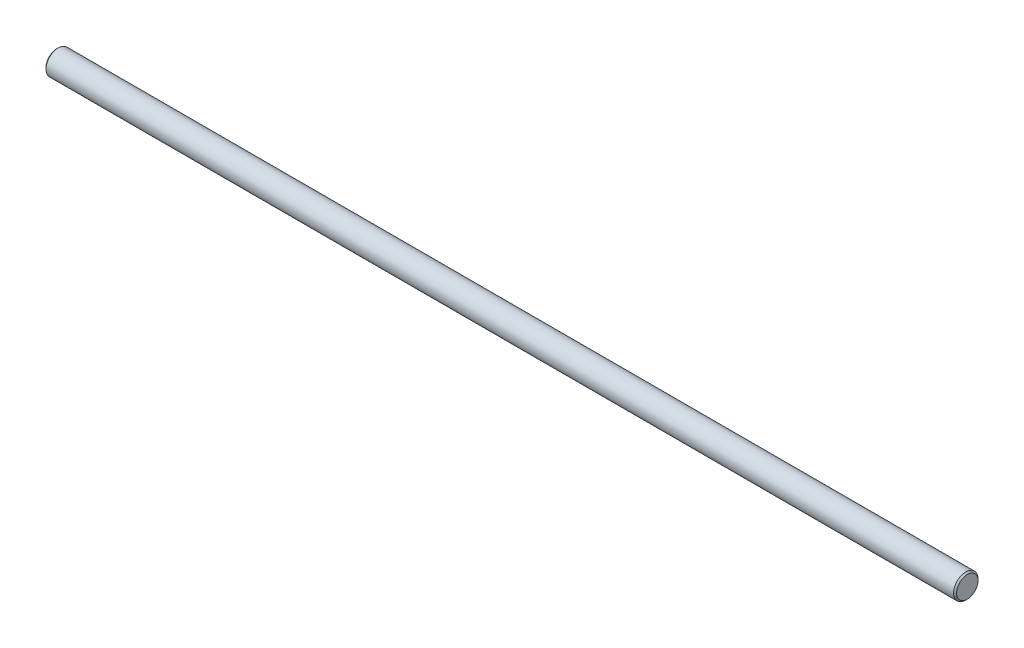
SolidWorks part; units mm, degrees
ref_plane "Alzado" through (0, 0, 0) normal (0, 0, 1) x (1, 0, 0)
ref_plane "Planta" through (0, 0, 0) normal (0, 1, 0) x (1, 0, 0)
ref_plane "Vista lateral" through (0, 0, 0) normal (1, 0, 0) x (0, 0, -1)
sketch "Croquis1" plane through (397.2152, 0, 0) normal (1, 0, 0) x (0, 0, -1)
  circle A2 centre (160.2806, -23.2373) radius 4
  dimension "D1" = 8
extrude "Saliente-Extruir1" add sketch "Croquis1" against normal up to surface (297.9 mm away)
chamfer "Chaflán1" distance 0.5 angle 45 2 edges at (397.2152, -19.2373, -160.2806) (99.3152, -23.2373, -164.2806)
